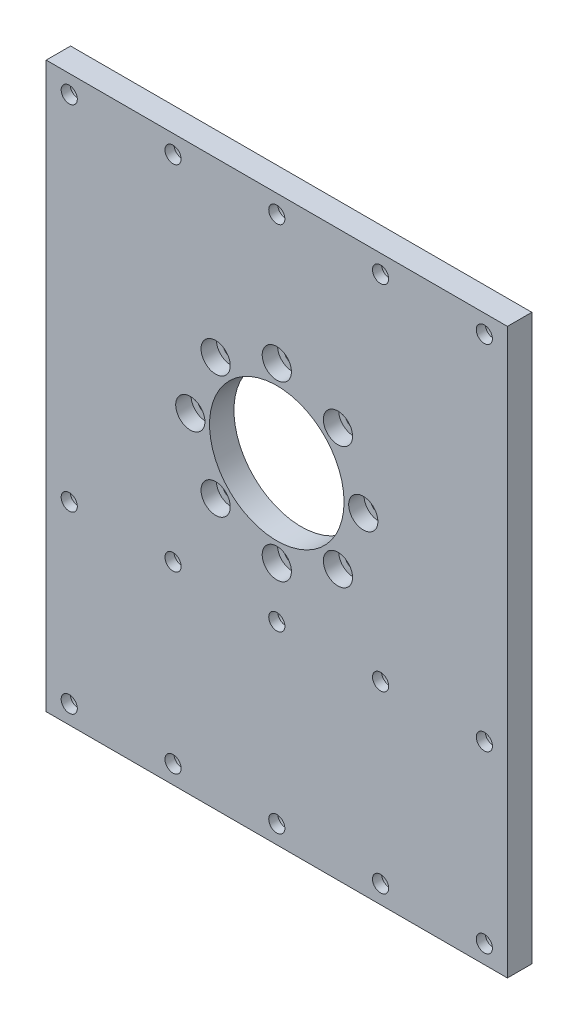
SolidWorks part; units mm, degrees
ref_plane "Front Plane" through (0, 0, 0) normal (1, 0, 0) x (0, 1, 0)
ref_plane "Top Plane" through (0, 0, 0) normal (0, 0, 1) x (0, 1, 0)
ref_plane "Right Plane" through (0, 0, 0) normal (0, 1, 0) x (-1, 0, 0)
sketch "Sketch1" plane through (0, 0, 0) normal (0, 0, 1) x (0, 1, 0)
  line L1 (-86, -60) -> (86, -60)
  line L2 (-86, -60) -> (-86, 60)
  line L3 (-86, 60) -> (86, 60)
  line L4 (86, -60) -> (86, 60)
  line L5 (-86, -60) -> (86, 60) construction
  line L6 (-86, 60) -> (86, -60) construction
  point P0 (0, 0)
  dimension "D1" = 172
  dimension "D2" = 120
extrude "Boss-Extrude1" add sketch "Sketch1" along normal blind 6.35
sketch "Sketch2" plane through (0, 0, 6.35) normal (0, 0, 1) x (1, 0, 0)
  circle A0 centre (0, 22.5) radius 2.1
  circle A1 centre (15.9099, 15.9099) radius 2.1
  circle A2 centre (22.5, 0) radius 2.1
  circle A3 centre (15.9099, -15.9099) radius 2.1
  circle A4 centre (0, -22.5) radius 2.1
  circle A5 centre (-15.9099, -15.9099) radius 2.1
  circle A6 centre (-22.5, 0) radius 2.1
  circle A7 centre (-15.9099, 15.9099) radius 2.1
  point P4 (16.3936, 19.0311)
  point P5 (0, 0)
  point P19 (0, 0)
  dimension "D2" = 4.2
  dimension "D1" = 22.5
  dimension "D3" = 8
hole_wizard "CBORE for M4 Hex Head Cap Screw1" positions "3DSketch1" profile "Sketch3" counterbore size "M4" standard "ISO" end condition through all
sketch3d "3DSketch1"
  point P0 (0, -22.5, 6.35)
  point P3 (-15.9099, -15.9099, 6.35)
  point P6 (-22.5, 0, 6.35)
  point P9 (-15.9099, 15.9099, 6.35)
  point P12 (0, 22.5, 6.35)
  point P15 (15.9099, 15.9099, 6.35)
  point P18 (22.5, 0, 6.35)
  point P21 (15.9099, -15.9099, 6.35)
sketch "Sketch3" plane through (0, -22.5, 6.35) normal (1, 0, 0) x (0, -1, 0)
  line L0 (0, 0) -> (0, 6.35)
  line L1 (0, 6.35) -> (2.1, 6.35)
  line L3 (2.1, 6.35) -> (2.1, 4)
  line L4 (2.1, 4) -> (3.8, 4)
  line L5 (3.8, 4) -> (3.8, 0)
  line L7 (3.8, 0) -> (0, 0)
  line L11 (0, -6.35) -> (0, 107.95) construction
  dimension "Thru Hole Dia." = 4.2
  dimension "Thru Hole Depth" = 6.35
  dimension "C'Bore Dia." = 7.6
  dimension "C'Bore Depth" = 4
sketch "Sketch4" plane through (0, 0, 6.35) normal (0, 0, 1) x (1, 0, 0)
  circle A0 centre (0, 0) radius 17.5
  dimension "D1" = 35
extrude "Cut-Extrude1" cut sketch "Sketch4" against normal through all
sketch "Sketch5" plane through (0, 0, 0) normal (0, 0, -1) x (1, 0, 0)
  line L0 (-60, 86) -> (60, 86) construction
  circle A0 centre (-54, 81.2375) radius 2.1
  circle A1 centre (-27, 81.2375) radius 2.1
  circle A2 centre (0, 81.2375) radius 2.1
  circle A3 centre (27, 81.2375) radius 2.1
  circle A4 centre (54, 81.2375) radius 2.1
  circle A5 centre (-54, 35.7125) radius 2.1
  circle A6 centre (-27, 35.7125) radius 2.1
  circle A7 centre (0, 35.7125) radius 2.1
  circle A8 centre (27, 35.7125) radius 2.1
  circle A9 centre (54, 35.7125) radius 2.1
  circle A10 centre (-54, -56.0625) radius 2.1
  circle A11 centre (-27, -56.0625) radius 2.1
  circle A12 centre (0, -56.0625) radius 2.1
  circle A13 centre (27, -56.0625) radius 2.1
  circle A14 centre (54, -56.0625) radius 2.1
  dimension "D1" = 4.2
  dimension "D2" = 54
  dimension "D3" = 4.7625
  dimension "D5" = 27
  dimension "D7" = 45.525
  dimension "D8" = 2
  dimension "D9" = 91.775
  dimension "D4" = 5
  dimension "D6" = 2
hole_wizard "CBORE for M4 Hex Head Cap Screw2" positions "3DSketch2" profile "Sketch6" counterbore size "M4" standard "ISO" end condition through all
sketch3d "3DSketch2"
  point P0 (-54, -81.2375, 0)
  point P3 (-27, -81.2375, 0)
  point P6 (0, -81.2375, 0)
  point P9 (27, -81.2375, 0)
  point P12 (54, -81.2375, 0)
  point P15 (-54, -35.7125, 0)
  point P18 (-27, -35.7125, 0)
  point P21 (0, -35.7125, 0)
  point P24 (27, -35.7125, 0)
  point P27 (54, -35.7125, 0)
  point P30 (-54, 56.0625, 0)
  point P33 (-27, 56.0625, 0)
  point P36 (0, 56.0625, 0)
  point P39 (27, 56.0625, 0)
  point P42 (54, 56.0625, 0)
sketch "Sketch6" plane through (-54, -81.2375, 0) normal (1, 0, 0) x (0, 1, 0)
  line L0 (0, 0) -> (0, 6.35)
  line L1 (0, 6.35) -> (2.1, 6.35)
  line L3 (2.1, 6.35) -> (2.1, 4)
  line L4 (2.1, 4) -> (3.8, 4)
  line L5 (3.8, 4) -> (3.8, 0)
  line L7 (3.8, 0) -> (0, 0)
  line L11 (0, -6.35) -> (0, 107.95) construction
  dimension "Thru Hole Dia." = 4.2
  dimension "Thru Hole Depth" = 6.35
  dimension "C'Bore Dia." = 7.6
  dimension "C'Bore Depth" = 4
sketch "Sketch7" plane through (0, 0, 6.35) normal (0, 0, 1) x (1, 0, 0)
  line L0 (60, -86) -> (60, 86) construction
  line L1 (60, 86) -> (-60, 86) construction
  line L2 (-60, 86) -> (-60, -86) construction
  line L3 (60, -86) -> (60, 86)
  line L4 (60, 86) -> (-60, 86)
  line L5 (-60, 86) -> (-60, -86)
  line L6 (-60, 60.825) -> (60, 60.825)
  circle A0 centre (54, 56.0625) radius 2.1 construction
  circle A1 centre (54, 56.0625) radius 2.1
  point P9 (60, 86)
  line M26 (60, 86) -> (-60, 86)
  line M27 (-60, 86) -> (-60, -86)
  dimension "D1" = 4.7625
extrude "Cut-Extrude2" cut sketch "Sketch7" against normal through all contours L6 L3 M27 M26
